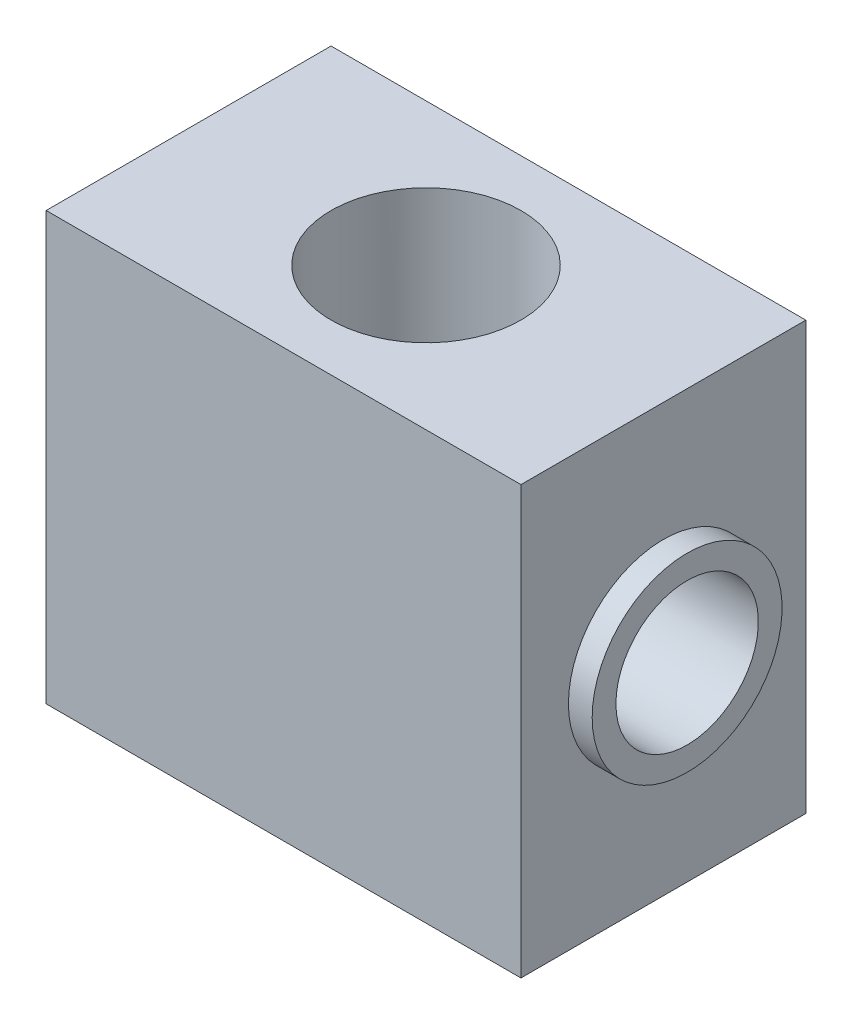
SolidWorks part; units mm, degrees
material "6061-T6 (SS)"
ref_plane "Front Plane" through (0, 0, 0) normal (0, 0, 1) x (1, 0, 0)
ref_plane "Top Plane" through (0, 0, 0) normal (0, 1, 0) x (1, 0, 0)
ref_plane "Right Plane" through (0, 0, 0) normal (1, 0, 0) x (0, 0, -1)
sketch "Sketch1" plane through (0, 0, 0) normal (0, 0, 1) x (1, 0, 0)
  line L0 (0, 0) -> (15.875, 0) construction
  line L1 (-15.875, 14.2875) -> (15.875, 14.2875)
  line L2 (-15.875, 14.2875) -> (-15.875, -14.2875)
  line L3 (-15.875, -14.2875) -> (15.875, -14.2875)
  line L4 (15.875, 14.2875) -> (15.875, -14.2875)
  line L5 (0, 0) -> (0, 14.2875) construction
  dimension "D1" = 28.575
  dimension "D2" = 31.75
extrude "Boss-Extrude1" add sketch "Sketch1" along normal mid plane 19.05
sketch "Sketch2" plane through (0, -14.2875, 0) normal (0, -1, 0) x (1, 0, 0)
  circle A0 centre (0, 0) radius 6.35
  dimension "D1" = 12.7
extrude "Cut-Extrude1" cut sketch "Sketch2" against normal through all
sketch "Sketch3" plane through (-15.875, 0, 0) normal (-1, 0, 0) x (0, 0, 1)
  circle A0 centre (0, 0) radius 4.7625
  dimension "D1" = 9.525
extrude "Cut-Extrude2" cut sketch "Sketch3" against normal through all
sketch "Sketch4" plane through (-15.875, 0, 0) normal (-1, 0, 0) x (0, 0, 1)
  circle A0 centre (0, 0) radius 6.35
  circle A1 centre (0, 0) radius 4.7625 construction
  circle A2 centre (0, 0) radius 4.7625
  dimension "D1" = 12.7
extrude "Boss-Extrude2" add sketch "Sketch4" along normal blind 1.5875
mirror "Mirror1" about plane through (0, 0, 0) normal (1, 0, 0) of "Boss-Extrude2"
